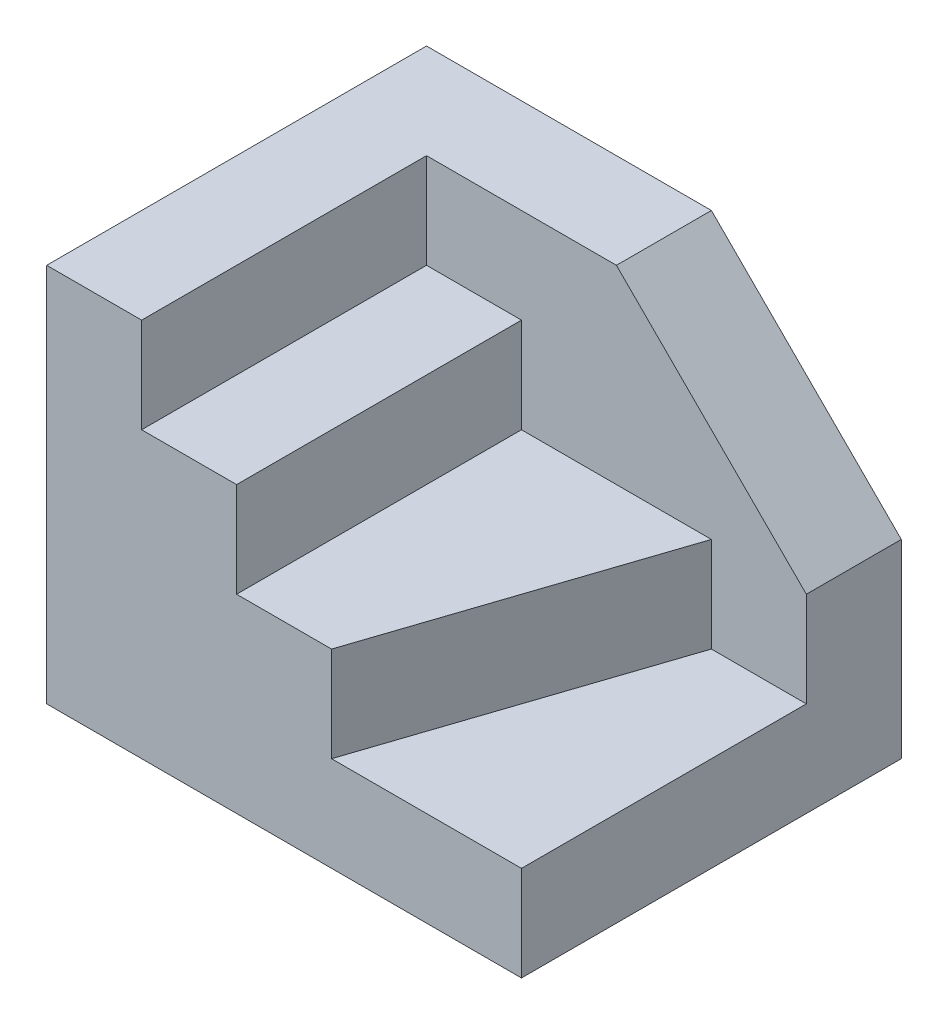
SolidWorks part; units mm, degrees
ref_plane "Front Plane" through (0, 0, 0) normal (0, 0, 1) x (1, 0, 0)
ref_plane "Top Plane" through (0, 0, 0) normal (0, 1, 0) x (1, 0, 0)
ref_plane "Right Plane" through (0, 0, 0) normal (1, 0, 0) x (0, 0, -1)
sketch "Sketch1" plane through (0, 0, 0) normal (0, 0, 1) x (1, 0, 0)
  line L0 (-20, 26.4815) -> (-20, -13.5185)
  line L1 (-20, -13.5185) -> (30, -13.5185)
  line L2 (30, -13.5185) -> (30, -3.5185)
  line L3 (30, -3.5185) -> (20, -3.5185)
  line L4 (20, -3.5185) -> (20, 6.4815)
  line L5 (20, 6.4815) -> (0, 6.4815)
  line L6 (0, 6.4815) -> (0, 16.4815)
  line L7 (0, 16.4815) -> (-10, 16.4815)
  line L8 (-10, 16.4815) -> (-10, 26.4815)
  line L9 (-10, 26.4815) -> (-20, 26.4815)
  dimension "D1" = 50
  dimension "D2" = 40
  dimension "D3" = 10
  dimension "D4" = 10
  dimension "D5" = 20
  dimension "D6" = 10
  dimension "D7" = 10
  dimension "D8" = 10
  dimension "D9" = 10
extrude "Boss-Extrude1" add sketch "Sketch1" along normal blind 30
sketch "Sketch2" plane through (0, 6.4815, 0) normal (0, 1, 0) x (1, 0, 0)
  line L0 (20, 0) -> (10, -30)
  line L1 (20, -30) -> (0, -30) construction
  line L2 (10, -30) -> (20, -30)
  line L3 (20, -30) -> (20, 0)
extrude "Cut-Extrude1" cut sketch "Sketch2" against normal blind 10
sketch "Sketch3" plane through (0, 0, 0) normal (0, 0, -1) x (-1, 0, 0)
  line L0 (20, 26.4815) -> (20, -13.5185)
  line L1 (20, -13.5185) -> (-30, -13.5185)
  line L2 (-30, -13.5185) -> (-30, 6.4815)
  line L3 (20, 26.4815) -> (-10, 26.4815)
  line L4 (-10, 26.4815) -> (-30, 6.4815)
extrude "Boss-Extrude2" add sketch "Sketch3" along normal blind 10
